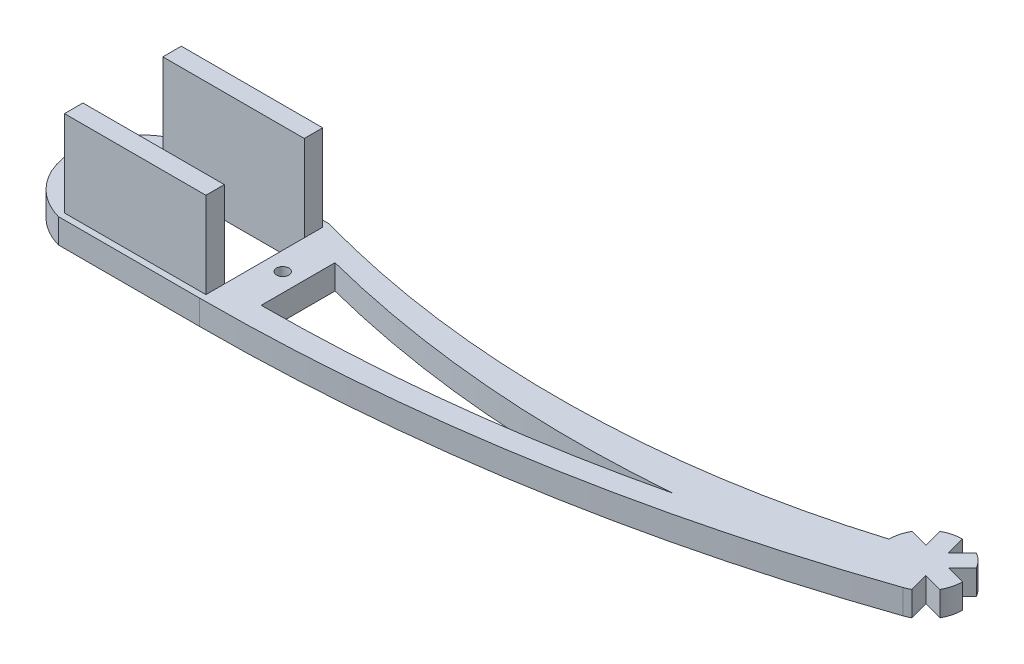
SolidWorks part; units mm, degrees
material "Plain Carbon Steel"
ref_plane "Front Plane" through (0, 0, 0) normal (0, 0, 1) x (1, 0, 0)
ref_plane "Top Plane" through (0, 0, 0) normal (0, 1, 0) x (1, 0, 0)
ref_plane "Right Plane" through (0, 0, 0) normal (1, 0, 0) x (0, 0, -1)
sketch "Sketch1" plane through (0, 0, 0) normal (0, 1, 0) x (1, 0, 0)
  line L0 (17.5, 5.5) -> (17.5, -6.5)
  line L1 (-11.5, -6.5) -> (11.5, -6.5)
  line L2 (-11.5, -6.5) -> (-11.5, -3)
  line L3 (-11.5, 6.5) -> (11.5, 6.5)
  line L4 (11.5, -6.5) -> (11.5, 6.5)
  line L5 (-11.5, -6.5) -> (11.5, 6.5) construction
  line L6 (-11.5, 6.5) -> (11.5, -6.5) construction
  line L7 (-11.5, -10.5) -> (11.5, -10.5)
  line L8 (-11.5, -6.5) -> (-11.5, 6.5)
  line L9 (-11.5, 10.5) -> (11.5, 10.5)
  line L10 (11.5, -6.5) -> (11.5, 6.5)
  line L11 (-11.5, -10.5) -> (11.5, 10.5) construction
  line L12 (-10.1522, 9.2694) -> (11.5, -10.5) construction
  line L13 (0, 0) -> (-19.5, 0) construction
  line L14 (-12.5, 3) -> (-11.5, 3)
  line L15 (-12.5, 3) -> (-12.5, -3)
  line L16 (-12.5, -3) -> (-11.5, -3)
  line L17 (-11.5, 3) -> (-11.5, 6.5)
  arc A0 (-11.5, 10.5) -> (-11.5, -10.5) centre (-8.6094, 0) ccw
  circle A1 centre (-14.5, 0) radius 1
  circle A2 centre (14.5, 0) radius 1
  arc A3 (11.5, -10.5) -> (109.4592, 5.944) centre (11.5, 289.5) ccw
  arc A4 (11.5, 10.5) -> (101.5, 11.6151) centre (54.5977, 164.5863) ccw
  arc A6 (109.4592, 5.944) -> (101.5, 11.6151) centre (107.5, 11.6151) ccw
  arc A7 (17.5, -6.5) -> (77.5, 0.5178) centre (17.5, 253.5) ccw
  arc A8 (17.5, 5.5) -> (77.5, 0.5178) centre (62.1856, 179.8651) ccw
  point P0 (0, 0)
  point P6 (0, 0)
  dimension "D1" = 2
  dimension "D10" = 2
  dimension "D11" = 160
  dimension "D12" = 300
  dimension "D13" = 12
  dimension "D16" = 260
  dimension "D17" = 180
  dimension "D19" = 1
  dimension "D2" = 23
  dimension "D3" = 4
  dimension "D4" = 3
  dimension "D5" = 6
  dimension "D6" = 13
  dimension "D7" = 8
  dimension "D8" = 1
  dimension "D9" = 3
  dimension "D14" = 90
  dimension "D15" = 6
  dimension "D18" = 60
extrude "Boss-Extrude1" add sketch "Sketch1" along normal blind 4 contours A3 A6 A4 L9 A0 L7 L16 L15 L14 L8 L3 L4 L1 L2 A1 A2 L0 A8 A7
sketch "Sketch2" plane through (0, 4, 0) normal (0, 1, 0) x (1, 0, 0)
  line L0 (11.5, -6.5) -> (11.5, 6.5) construction
  line L1 (-11.5, 6.5) -> (11.5, 6.5)
  line L2 (-11.5, 6.5) -> (-11.5, 9.5)
  line L3 (-11.5, 9.5) -> (11.5, 9.5)
  line L4 (11.5, 6.5) -> (11.5, 9.5)
  line L5 (-11.5, -6.5) -> (11.5, -6.5)
  line L6 (-11.5, -6.5) -> (-11.5, -9.5)
  line L7 (-11.5, -9.5) -> (11.5, -9.5)
  line L8 (11.5, -6.5) -> (11.5, -9.5)
  line L9 (-11.5, 3) -> (-11.5, 6.5) construction
  line L10 (-11.5, -6.5) -> (-11.5, -3) construction
  line M9 (-11.5, 6.5) -> (11.5, 6.5)
  line M11 (11.5, -6.5) -> (-11.5, -6.5)
  dimension "D1" = 3
  dimension "D2" = 3
extrude "Boss-Extrude2" add sketch "Sketch2" along normal blind 14 contours L8 L6 L7 M11 | L4 L3 L2 M9
sketch "Sketch3" plane through (0, 4, 0) normal (0, 1, 0) x (1, 0, 0)
  line L0 (101.5, 11.6151) -> (107.5, 11.6151) construction
  line L1 (107.5, 11.6151) -> (103.2574, 15.8578) construction
  line L2 (105.3787, 13.7365) -> (102.2767, 14.5676)
  line L3 (105.3787, 13.7365) -> (104.5475, 16.8384)
  line L4 (108.2765, 14.5129) -> (110.5473, 16.7837)
  line L5 (108.2765, 14.5129) -> (107.4453, 17.6149)
  line L6 (110.3978, 12.3916) -> (113.4998, 11.5604)
  line L7 (110.3978, 12.3916) -> (112.6686, 14.6624)
  line L8 (109.6213, 9.4938) -> (110.4525, 6.3918)
  line L9 (109.6213, 9.4938) -> (112.7233, 8.6626)
  line L10 (106.7235, 8.7174) -> (104.4527, 6.4466) [skipped]
  line L11 (106.7235, 8.7174) -> (107.5547, 5.6154) [skipped]
  line L12 (104.6022, 10.8387) -> (101.5002, 11.6698) [skipped]
  line L13 (104.6022, 10.8387) -> (102.3314, 8.5679) [skipped]
  arc A0 (109.4592, 5.944) -> (101.5, 11.6151) centre (107.5, 11.6151) ccw construction
  arc A1 (104.5475, 16.8384) -> (102.2767, 14.5676) centre (107.5, 11.6151) ccw
  arc A2 (110.5473, 16.7837) -> (107.4453, 17.6149) centre (107.5, 11.6151) ccw
  arc A3 (113.4998, 11.5604) -> (112.6686, 14.6624) centre (107.5, 11.6151) ccw
  arc A4 (110.4525, 6.3918) -> (112.7233, 8.6626) centre (107.5, 11.6151) ccw
  arc A5 (104.4527, 6.4466) -> (107.5547, 5.6154) centre (107.5, 11.6151) ccw [skipped]
  arc A6 (101.5002, 11.6698) -> (102.3314, 8.5679) centre (107.5, 11.6151) ccw [skipped]
  arc M8 (109.4592, 5.944) -> (101.5, 11.6151) centre (107.5, 11.6151) ccw
  dimension "D1" = 45
  dimension "D2" = 60
  dimension "D3" = 3
  dimension "D4" = 6
extrude "Cut-Extrude1" cut sketch "Sketch3" against normal through all contours L2 L3 M8 | L5 L4 M8 | L7 L6 M8 | L9 L8 M8
